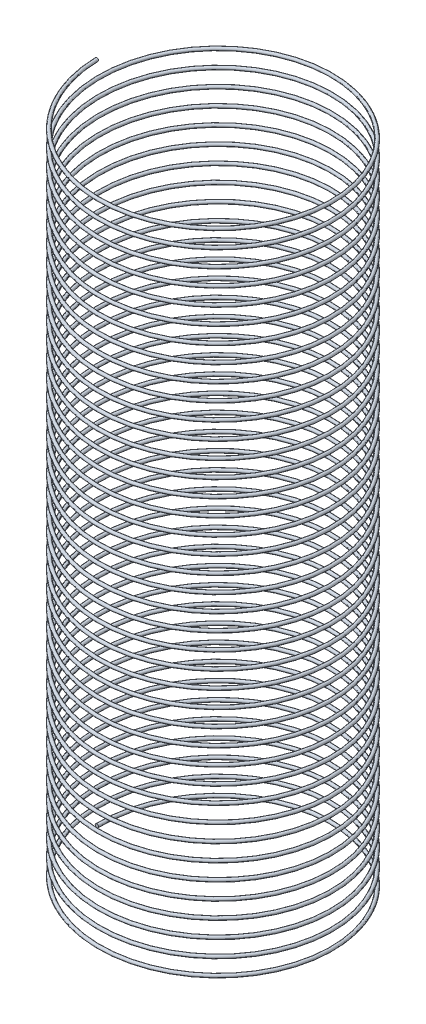
SolidWorks part; units mm, degrees
material "硅橡胶板 "
ref_plane "前视基准面" through (0, 0, 0) normal (0, 0, 1) x (1, 0, 0)
ref_plane "上视基准面" through (0, 0, 0) normal (0, 1, 0) x (1, 0, 0)
ref_plane "右视基准面" through (0, 0, 0) normal (1, 0, 0) x (0, 0, -1)
sketch "草图1" plane through (0, 0, 0) normal (0, 1, 0) x (1, 0, 0)
  circle A0 centre (0, 0) radius 35
  dimension "D1" = 70
curve "螺旋线/涡状线1" pitch 5 height 200 turns 40
sweep "扫描1" add path "螺旋线/涡状线1" circular profile diameter 1 parameters "D3"=1
